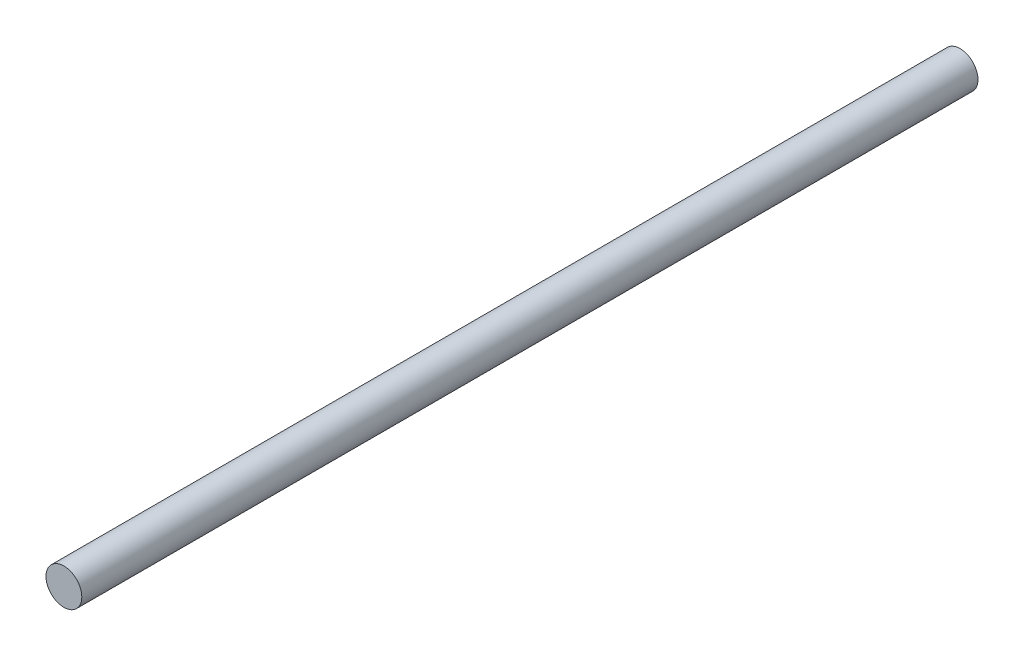
SolidWorks part; units mm, degrees
material "AISI Тип 316L нержавеющая сталь"
ref_plane "Front" through (0, 0, 0) normal (0, 0, 1) x (1, 0, 0)
ref_plane "Top" through (0, 0, 0) normal (0, 1, 0) x (1, 0, 0)
ref_plane "Right" through (0, 0, 0) normal (1, 0, 0) x (0, 0, -1)
sketch "Эскиз1" plane through (0, 0, 0) normal (0, 0, 1) x (1, 0, 0)
  circle A0 centre (0, 0) radius 4
  dimension "D1" = 8
extrude "Бобышка-Вытянуть1" add sketch "Эскиз1" against normal blind 200
sketch "Эскиз2" plane through (0, 0, 0) normal (0, 0, 1) x (1, 0, 0)
  circle A0 centre (0, 0) radius 4
  dimension "D1" = 8
curve "Спираль1" pitch 2 height 200 turns 100
sketch "Эскиз3" plane through (0, 0, 0) normal (0, 1, 0) x (1, 0, 0)
  line L0 (-4, -0.6329) -> (-4, 0.6329)
  line L1 (-4, 0.6329) -> (-3, 0.365)
  line L2 (-3, 0.365) -> (-3, -0.365)
  line L3 (-3, -0.365) -> (-4, -0.6329)
  line L4 (-4, 0) -> (4, 0) construction
  point P2 (-4, 0)
  dimension "D1" = 0.73
  dimension "D2" = 15
  dimension "D3" = 15
  dimension "D4" = 1
